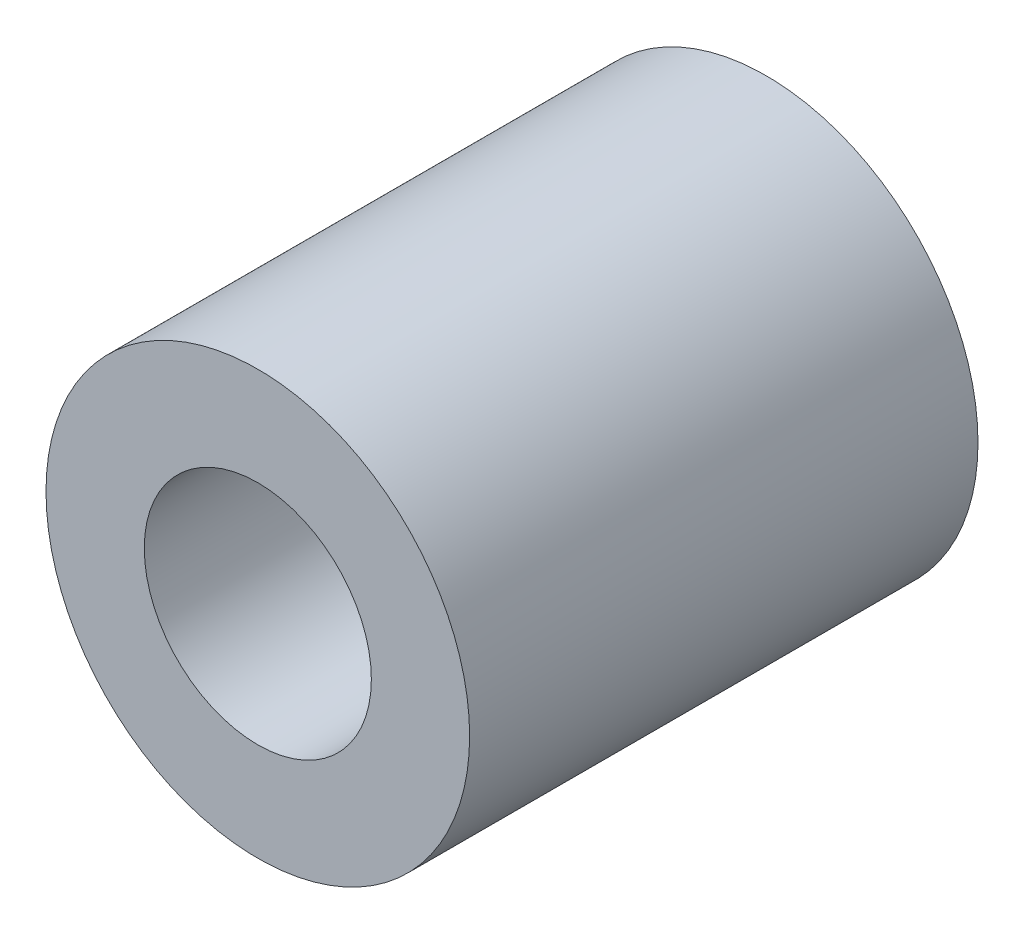
SolidWorks part; units mm, degrees
material "6061 Alloy"
ref_plane "Front Plane" through (0, 0, 0) normal (0, 0, 1) x (1, 0, 0)
ref_plane "Top Plane" through (0, 0, 0) normal (0, 1, 0) x (1, 0, 0)
ref_plane "Right Plane" through (0, 0, 0) normal (1, 0, 0) x (0, 0, -1)
sketch "Sketch1" plane through (0, 0, 0) normal (0, 0, 1) x (1, 0, 0)
  circle A0 centre (0, 0) radius 4.7625
  circle A1 centre (0, 0) radius 2.5527
  dimension "D1" = 9.525
  dimension "D2" = 5.1054
extrude "Boss-Extrude1" add sketch "Sketch1" along normal blind 11.43
